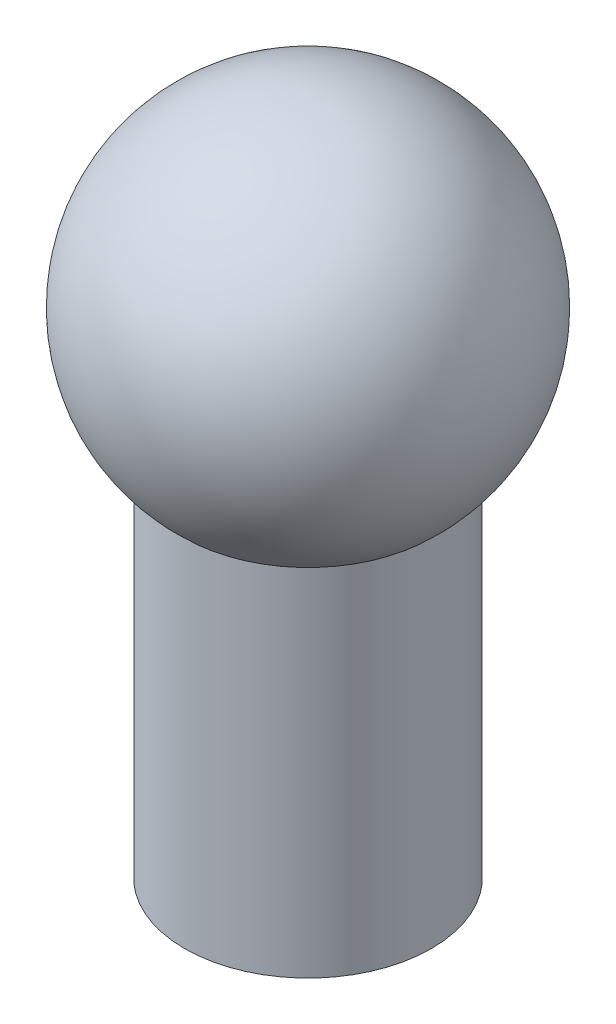
SolidWorks part; units mm, degrees
ref_plane "前视基准面" through (0, 0, 0) normal (0, 0, 1) x (1, 0, 0)
ref_plane "上视基准面" through (0, 0, 0) normal (0, 1, 0) x (1, 0, 0)
ref_plane "右视基准面" through (0, 0, 0) normal (1, 0, 0) x (0, 0, -1)
other "Configuration Table"
sketch "草图1" plane through (0, 0, 0) normal (0, 1, 0) x (1, 0, 0)
  circle A0 centre (0, 0) radius 10
  dimension "D1" = 20
extrude "凸台-拉伸1" add sketch "草图1" along normal blind 40 contours A0
sketch "草图2" plane through (0, 40, 0) normal (0, 1, 0) x (1, 0, 0)
  line L0 (0, -15) -> (0, 15)
  arc A0 (0, -15) -> (0, 15) centre (0, 0) ccw
  dimension "D1" = 30
revolve "旋转2" add sketch "草图2" angle 360 about L0
